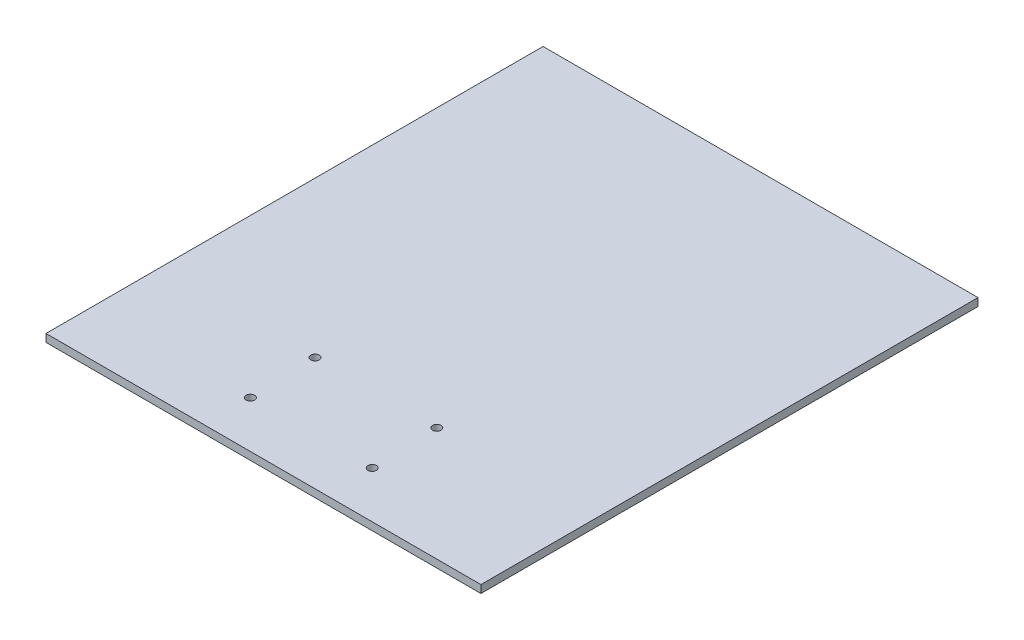
SolidWorks part; units mm, degrees
ref_plane "Front Plane" through (0, 0, 0) normal (0, 0, 1) x (1, 0, 0)
ref_plane "Top Plane" through (0, 0, 0) normal (0, 1, 0) x (1, 0, 0)
ref_plane "Right Plane" through (0, 0, 0) normal (1, 0, 0) x (0, 0, -1)
sketch "Sketch1" plane through (0, 0, 0) normal (0, 1, 0) x (1, 0, 0)
  line L1 (0, 0) -> (-177.8, 0)
  line L2 (0, 0) -> (0, -203.2)
  line L3 (0, -203.2) -> (-177.8, -203.2)
  line L4 (-177.8, 0) -> (-177.8, -203.2)
  dimension "D1" = 177.8
  dimension "D2" = 203.2
extrude "Boss-Extrude1" add sketch "Sketch1" along normal blind 3.175
hole_wizard "Tap Drill for #8-36 Tap1" positions "Sketch3" profile "Sketch2" hole size "#8-36" standard "ANSI Inch" end condition up to next
sketch "Sketch3" plane through (0, 3.175, 0) normal (0, 1, 0) x (1, 0, 0)
  point P0 (-114.3, -156.7271)
  point P3 (-64.5116, -156.7271)
  point P15 (-113.2884, -184.15)
  point P18 (-63.5, -184.15)
sketch "Sketch2" plane through (-114.3, 3.175, 156.7271) normal (1, 0, 0) x (0, 0, 1)
  line L0 (0, 0) -> (0, 3.175)
  line L1 (0, 3.175) -> (1.7272, 3.175)
  line L2 (1.7272, 3.175) -> (1.7272, 0)
  line L5 (1.7272, 0) -> (0, 0)
  line L11 (0, -6.35) -> (0, 107.95) construction
  dimension "Thru Hole Dia." = 3.4544
  dimension "Thru Hole Depth" = 3.175
